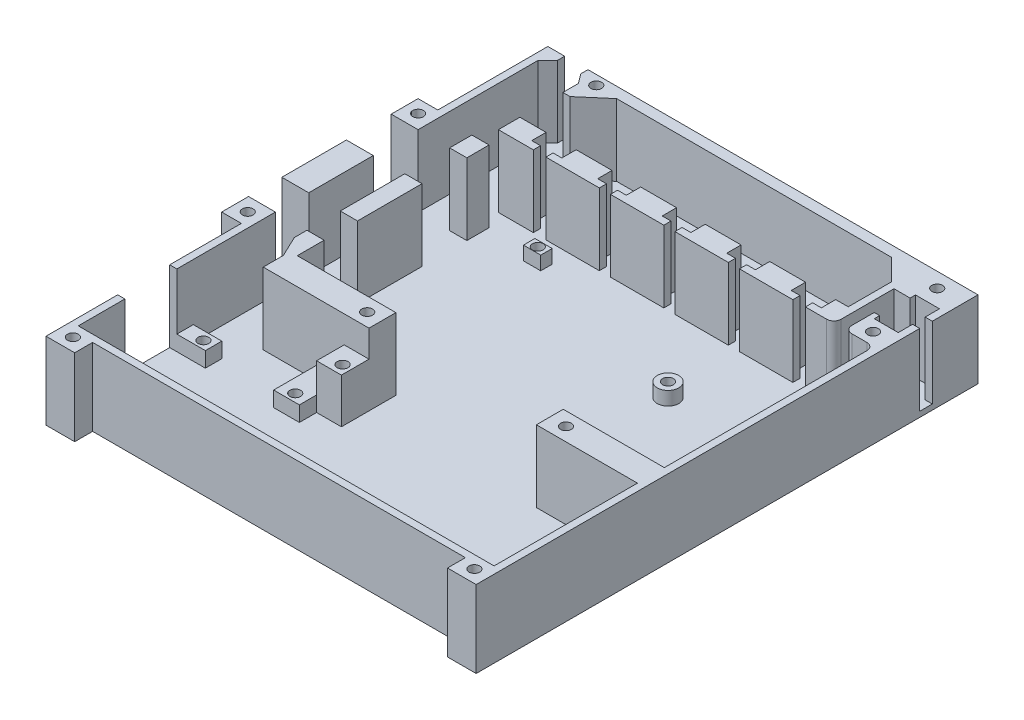
SolidWorks part; units mm, degrees
ref_plane "Front Plane" through (0, 0, 0) normal (0, 0, 1) x (1, 0, 0)
ref_plane "Top Plane" through (0, 0, 0) normal (0, 1, 0) x (1, 0, 0)
ref_plane "Right Plane" through (0, 0, 0) normal (1, 0, 0) x (0, 0, -1)
sketch "Sketch1" plane through (0, 0, 0) normal (0, 1, 0) x (1, 0, 0)
  line L0 (-60, -67.5) -> (-60, -72.5)
  line L1 (-52, -67.5) -> (52, -67.5)
  line L2 (-60, -67.5) -> (-60, -18)
  line L3 (-60, 67.5) -> (60, 67.5)
  line L4 (60, -67.5) -> (60, 67.5)
  line L5 (-60, -67.5) -> (60, 67.5) construction
  line L6 (-60, 67.5) -> (60, -67.5) construction
  line L7 (-60, -72.5) -> (-52, -72.5)
  line L8 (-52, -72.5) -> (-52, -67.5)
  line L9 (0, 0) -> (0, -67.5) construction
  line L10 (60, -67.5) -> (60, -72.5)
  line L11 (52, -72.5) -> (52, -67.5)
  line L12 (60, -72.5) -> (52, -72.5)
  line L13 (-60, -18) -> (-65.5, -18)
  line L14 (-65.5, -18) -> (-65.5, -10.5)
  line L16 (-60, 7.8) -> (60, 7.8) construction
  line L18 (-65.5, -1.2) -> (-60, -1.2)
  line L25 (-60, -10.5) -> (-60, -1.2)
  line L26 (-65.5, -1.2) -> (-65.5, 7.8)
  line L29 (-65.5, -10.5) -> (-60, -10.5)
  line L33 (-65.5, -10.5) -> (-65.5, -4.4868) construction
  line L34 (-65.5, 7.8) -> (-65.5, 16.8)
  line L35 (-65.5, 16.8) -> (-60, 16.8)
  line L36 (-60, 16.8) -> (-60, 29.3)
  line L37 (-60, 29.3) -> (-65.5, 29.3)
  line L38 (-65.5, 29.3) -> (-65.5, 36.8)
  line L39 (-65.5, 36.8) -> (-60, 36.8)
  line L40 (-60, 36.8) -> (-60, 67.5)
  point P0 (0, 0)
  point P30 (-65.5, 7.8)
  dimension "D1" = 120
  dimension "D2" = 135
  dimension "D3" = 5
  dimension "D4" = 8
  dimension "D5" = 54.5
  dimension "D7" = 5.5
  dimension "D8" = 9
  dimension "D9" = 59.7
  dimension "D10" = 9.3
extrude "Boss-Extrude1" add sketch "Sketch1" along normal blind 1.5
sketch "Sketch2" plane through (0, 1.5, 0) normal (0, 1, 0) x (1, 0, 0)
  line L0 (-58, 62.8) -> (-58, 29.3)
  line L1 (-58, -65.5) -> (58, -65.5)
  line L2 (58, -65.5) -> (58, -25.5)
  line L4 (-60, 29.3) -> (-58, 29.3)
  line L5 (-60, 16.8) -> (-58, 16.8)
  line L6 (-58, 16.8) -> (-58, -1.2)
  line L7 (-60, -1.2) -> (-58, -1.2)
  line L8 (-60, -10.5) -> (-58, -10.5)
  line L9 (-58, -10.5) -> (-58, -38)
  line L10 (-55.3, 65.5) -> (-55.3, 67.5)
  line L11 (-48.8, 67.5) -> (-48.8, 65.5)
  line L12 (-55.3, 65.5) -> (-58, 62.8)
  line L13 (-55.3, 67.5) -> (-60, 67.5)
  line L14 (-55.3, 67.5) -> (-48.8, 67.5) construction
  line L15 (-48.8, 65.5) -> (-46.8, 62.8)
  line L16 (-58, 62.8) -> (-46.8, 62.8) construction
  line L17 (-48.8, 67.5) -> (-46.8, 67.5) construction
  line L18 (-46.8, 67.5) -> (-46.8, 58.5) construction
  line L19 (-46.8, 62.8) -> (-46.8, 58.5)
  line L20 (60, -72.5) -> (60, 67.5)
  line L21 (60, 67.5) -> (-60, 67.5)
  line L22 (-60, 67.5) -> (-60, 36.8)
  line L23 (-60, 29.3) -> (-60, 16.8)
  line L24 (-60, 67.5) -> (-60, 36.8)
  line L25 (-60, 36.8) -> (-65.5, 36.8)
  line L26 (-60, 36.8) -> (-65.5, 36.8)
  line L27 (-65.5, 36.8) -> (-65.5, 29.3)
  line L28 (-65.5, 16.8) -> (-65.5, -1.2)
  line L29 (-65.5, -1.2) -> (-60, -1.2)
  line L30 (-60, -1.2) -> (-60, -10.5)
  line L31 (-60, -10.5) -> (-65.5, -10.5)
  line L32 (-65.5, -10.5) -> (-65.5, -18)
  line L33 (-65.5, -18) -> (-60, -18)
  line L34 (-60, -18) -> (-60, -72.5)
  line L35 (-60, -72.5) -> (-52, -72.5)
  line L36 (-52, -72.5) -> (-52, -67.5)
  line L37 (-52, -67.5) -> (52, -67.5)
  line L38 (52, -67.5) -> (52, -72.5)
  line L39 (52, -72.5) -> (60, -72.5)
  line L40 (60, -72.5) -> (60, 51.25)
  line L41 (60, 67.5) -> (-48.8, 67.5)
  line L48 (-65.5, 16.8) -> (-65.5, -1.2)
  line L49 (-65.5, -1.2) -> (-60, -1.2)
  line L51 (-60, -10.5) -> (-65.5, -10.5)
  line L52 (-65.5, -10.5) -> (-65.5, -18)
  line L53 (-65.5, -18) -> (-60, -18)
  line L54 (-60, -18) -> (-60, -38)
  line L55 (-60, -72.5) -> (-52, -72.5)
  line L56 (-52, -72.5) -> (-52, -67.5)
  line L57 (-52, -67.5) -> (52, -67.5)
  line L58 (52, -67.5) -> (52, -72.5)
  line L59 (52, -72.5) -> (60, -72.5)
  line L60 (-46.8, 58.5) -> (-44.8, 58.5)
  line L61 (-44.8, 58.5) -> (-37.8, 64.5)
  line L62 (-46.8, 58.5) -> (-46.8, 46.5) construction
  line L63 (-46.8, 46.5) -> (-39.5, 46.5)
  line L64 (-39.5, 46.5) -> (-39.5, 42.5)
  line L65 (-39.5, 42.5) -> (-37.05, 42.5)
  line L66 (-37.05, 42.5) -> (-37.05, 40.5)
  line L67 (-37.05, 40.5) -> (-46.8, 40.5)
  line L68 (-46.8, 40.5) -> (-46.8, 46.5)
  line L69 (-46.8, 52.5) -> (-35.3, 52.5) construction
  line L70 (-35.3, 52.5) -> (-35.3, 40.5) construction
  line L71 (-35.3, 40.5) -> (-37.05, 40.5) construction
  line L78 (-33.55, 42.5) -> (-33.55, 40.5)
  line L79 (-31.1, 42.5) -> (-33.55, 42.5)
  line L80 (-31.1, 46.5) -> (-31.1, 42.5)
  line L81 (-31.1, 46.5) -> (-21.1, 46.5)
  line L82 (-26.1, 46.5) -> (-26.1, 40.6) construction
  line L83 (-18.65, 42.5) -> (-18.65, 40.5)
  line L84 (-21.1, 42.5) -> (-18.65, 42.5)
  line L85 (-21.1, 46.5) -> (-21.1, 42.5)
  line L86 (-33.55, 40.5) -> (-18.65, 40.5)
  line L87 (-15.55, 40.5) -> (-0.65, 40.5)
  line L88 (-0.65, 42.5) -> (-0.65, 40.5)
  line L89 (-3.1, 42.5) -> (-0.65, 42.5)
  line L90 (-3.1, 46.5) -> (-3.1, 42.5)
  line L91 (-13.1, 46.5) -> (-3.1, 46.5)
  line L92 (-13.1, 46.5) -> (-13.1, 42.5)
  line L93 (-13.1, 42.5) -> (-15.55, 42.5)
  line L94 (-15.55, 42.5) -> (-15.55, 40.5)
  line L95 (2.45, 40.5) -> (17.35, 40.5)
  line L96 (17.35, 42.5) -> (17.35, 40.5)
  line L97 (14.9, 42.5) -> (17.35, 42.5)
  line L98 (14.9, 46.5) -> (14.9, 42.5)
  line L99 (4.9, 46.5) -> (14.9, 46.5)
  line L100 (4.9, 46.5) -> (4.9, 42.5)
  line L101 (4.9, 42.5) -> (2.45, 42.5)
  line L102 (2.45, 42.5) -> (2.45, 40.5)
  line L103 (20.45, 40.5) -> (35.35, 40.5)
  line L104 (35.35, 42.5) -> (35.35, 40.5)
  line L105 (32.9, 42.5) -> (35.35, 42.5)
  line L106 (32.9, 46.5) -> (32.9, 42.5)
  line L107 (22.9, 46.5) -> (32.9, 46.5)
  line L108 (22.9, 46.5) -> (22.9, 42.5)
  line L109 (22.9, 42.5) -> (20.45, 42.5)
  line L110 (20.45, 42.5) -> (20.45, 40.5)
  line L111 (35.35, 40.5) -> (37.1, 40.5) construction
  line L112 (37.1, 40.5) -> (37.1, 46.5) construction
  line L113 (38.85, 42.5) -> (38.85, 40.5)
  line L114 (41.3, 42.5) -> (38.85, 42.5)
  line L115 (41.3, 46.5) -> (41.3, 42.5)
  line L116 (38.85, 40.5) -> (44.8, 40.5)
  line L117 (41.3, 46.5) -> (44.8, 46.5)
  line L118 (46.8, 46.5) -> (46.8, 42.5)
  line L119 (46.8, 46.5) -> (46.8, 57.25)
  line L120 (46.8, 57.25) -> (51.3, 57.25)
  line L121 (51.3, 57.25) -> (51.3, 58.75)
  line L122 (51.3, 58.75) -> (58, 58.75)
  line L123 (44.8, 46.5) -> (44.8, 58.5)
  line L124 (58, 54.75) -> (60, 54.75)
  line L125 (58, 51.25) -> (60, 51.25)
  line L126 (58, 54.75) -> (58, 58.75)
  line L127 (60, 54.75) -> (60, 67.5)
  line L128 (44.8, 58.5) -> (38.8, 64.5)
  line L129 (38.8, 64.5) -> (-37.8, 64.5)
  line L130 (60, 54.75) -> (60, 51.25) construction
  line L131 (60, 53) -> (46.8, 53) construction
  line L132 (49.8, 48.75) -> (51.3, 48.75)
  line L133 (51.3, 48.75) -> (51.3, 47.25)
  line L134 (51.3, 47.25) -> (58, 47.25)
  line L135 (49.8, 48.75) -> (49.8, 42.5)
  line L136 (51.8, 40.5) -> (56, 40.5)
  line L137 (58, 47.25) -> (58, 51.25)
  line L138 (-46.8, 40.5) -> (-46.8, 35.5) construction
  line L139 (-46.8, 35.5) -> (-49.2, 35.5)
  line L140 (-49.2, 35.5) -> (-49.2, 29.3)
  line L141 (-49.2, 29.3) -> (-44.4, 29.3)
  line L142 (-44.4, 29.3) -> (-44.4, 35.5)
  line L143 (-44.4, 35.5) -> (-46.8, 35.5)
  line L144 (-46.8, 29.3) -> (-46.8, 35.5) construction
  line L145 (-58, 29.3) -> (-49.2, 29.3) construction
  line L146 (-58, 16.8) -> (-49.2, 16.8) construction
  line L147 (-58, -10.5) -> (-49.2, -10.5) construction
  line L148 (-49.2, 16.8) -> (-44.4, 16.8)
  line L149 (-49.2, 16.8) -> (-49.2, -1.2)
  line L150 (-49.2, -1.2) -> (-44.4, -1.2)
  line L151 (-44.4, 16.8) -> (-44.4, -1.2)
  line L152 (-49.2, -10.5) -> (-44.4, -10.5)
  line L153 (-44.4, -10.5) -> (-44.4, -18)
  line L154 (-44.4, -18) -> (-16.9, -18)
  line L155 (-16.9, -18) -> (-16.9, -25.5)
  line L156 (-16.9, -25.5) -> (-46.4, -25.5)
  line L157 (-46.4, -25.5) -> (-46.4, -19.9)
  line L158 (-46.4, -19.9) -> (-49.2, -14)
  line L159 (-49.2, -14) -> (-49.2, -10.5)
  line L160 (-60, -18) -> (-44.4, -18) construction
  line L161 (-44.4, -10.5) -> (-44.4, -1.2) construction
  line L162 (-44.4, 16.8) -> (-44.4, 29.3) construction
  line L163 (58, -18) -> (29.8, -18)
  line L164 (29.8, -18) -> (29.8, -25.5)
  line L165 (29.8, -25.5) -> (58, -25.5)
  line L166 (58, -18) -> (58, 38.5)
  line L167 (-60, -52.5) -> (-58, -52.5)
  line L168 (-58, -38) -> (-60, -38)
  line L169 (-60, -52.5) -> (-60, -72.5)
  line L170 (-58, -52.5) -> (-58, -65.5)
  line L187 (-65.5, 36.8) -> (-65.5, 29.3)
  line L188 (-65.5, 29.3) -> (-60, 29.3)
  line L189 (-65.5, 29.3) -> (-60, 29.3)
  line L190 (-60, 16.8) -> (-65.5, 16.8)
  line L191 (-60, 16.8) -> (-65.5, 16.8)
  arc A0 (46.8, 42.5) -> (44.8, 40.5) centre (44.8, 42.5) cw
  arc A1 (56, 40.5) -> (58, 38.5) centre (56, 38.5) cw
  arc A2 (49.8, 42.5) -> (51.8, 40.5) centre (51.8, 42.5) ccw
  point P140 (-59, -52.5)
  dimension "D20" = 2
  dimension "D28" = 2
  dimension "D4" = 2
  dimension "D5" = 2
  dimension "D6" = 20
  dimension "D7" = 6.5
  dimension "D8" = 2
  dimension "D9" = 9
  dimension "D10" = 2
  dimension "D11" = 6
  dimension "D12" = 2
  dimension "D13" = 4.2
  dimension "D14" = 11.5
  dimension "D15" = 10
  dimension "D16" = 1.75
  dimension "D17" = 4
  dimension "D18" = 1.75
  dimension "D19" = 5.5
  dimension "D21" = 2
  dimension "D22" = 10.75
  dimension "D23" = 4.5
  dimension "D24" = 1.5
  dimension "D25" = 4
  dimension "D26" = 3.5
  dimension "D27" = 3
  dimension "D29" = 4.8
  dimension "D30" = 6.2
  dimension "D31" = 3.5
  dimension "D32" = 7.5
  dimension "D33" = 2
  dimension "D34" = 29.5
  dimension "D35" = 28.2
  dimension "D36" = 14.5
  dimension "D1" = 0
extrude "Boss-Extrude2" add sketch "Sketch2" along normal blind 20
sketch "Sketch3" plane through (0, 21.5, 0) normal (0, 1, 0) x (1, 0, 0)
  line L2 (29.8, -21.75) -> (34.3, -21.75) construction
  line L3 (29.8, -18) -> (29.8, -25.5) construction
  line L4 (-56, -72.5) -> (-56, -69) construction
  line L5 (-60, -72.5) -> (-52, -72.5) construction
  line L6 (56, -72.5) -> (56, -69) construction
  line L7 (52, -72.5) -> (60, -72.5) construction
  circle A0 centre (52.7747, 63.3545) radius 1.5
  circle A1 centre (-43.8427, 64.8545) radius 1.5
  circle A2 centre (-61.8793, 33.1911) radius 1.5
  circle A3 centre (-61.8793, -14.3376) radius 1.5
  circle A4 centre (54.2747, 43.9451) radius 1.5
  circle A5 centre (-21.0296, -21.8624) radius 1.5
  circle A6 centre (34.3, -21.75) radius 1.5
  circle A7 centre (-56, -69) radius 1.5
  circle A8 centre (56, -69) radius 1.5
  point P10 (-21.0296, -21.8624)
  point P12 (-61.8793, 33.5924)
  point P14 (-61.8793, -14.3376)
  point P15 (-61.75, 33.1911)
  point P31 (-21.4, -28.75)
  dimension "D2" = 4.5
extrude "Cut-Extrude1" cut sketch "Sketch3" against normal blind 20
sketch "Sketch4" plane through (0, 1.5, 0) normal (0, 1, 0) x (1, 0, 0)
  line L0 (-60, 33.9) -> (-29.2, 33.9) construction
  line L1 (-60, 67.5) -> (-60, 40.6) construction
  line L2 (-29.2, 33.9) -> (-29.2, 67.5) construction
  line L3 (60, 67.5) -> (-48.8, 67.5) construction
  line L4 (-44.4, 35.5) -> (-31.6143, 35.5) construction
  line L5 (-31.6143, 32.3) -> (-26.7857, 32.3)
  line L6 (-31.6143, 32.3) -> (-31.6143, 35.5)
  line L7 (-31.6143, 35.5) -> (-26.7857, 35.5)
  line L8 (-26.7857, 32.3) -> (-26.7857, 35.5)
  line L9 (-31.6143, 32.3) -> (-26.7857, 35.5) construction
  line L10 (-31.6143, 35.5) -> (-26.7857, 32.3) construction
  line L11 (-60, -14.4) -> (-30.3, -14.4) construction
  line L12 (-30.3, -14.4) -> (51.8, -14.4) construction
  line L13 (-60, -18) -> (-60, -38) construction
  line L14 (-30.3, -14.4) -> (-30.3, -67.5) construction
  line L15 (-52, -67.5) -> (52, -67.5) construction
  line L16 (51.8, -14.4) -> (58, -14.4) construction
  line L22 (-16.9, -18) -> (-44.4, -18) construction
  line L23 (-33.1673, -18) -> (-27.3378, -18)
  line L24 (58, 38.5) -> (58, -18) construction
  line L25 (58, -18) -> (29.8, -18) construction
  line L26 (49.4239, -18) -> (54.0138, -18)
  line L27 (49.4239, -18) -> (49.4239, -12.2974)
  line L28 (49.4239, -12.2974) -> (54.0138, -12.2974)
  line L29 (54.0138, -18) -> (54.0138, -12.2974)
  line L30 (-33.1673, -18) -> (-33.1673, -12.2974)
  line L31 (-33.1673, -12.2974) -> (-27.3378, -12.2974)
  line L32 (-27.3378, -18) -> (-27.3378, -12.2974)
  line L33 (-30.3, -14.4) -> (21.5448, -8.3205) construction
  line L34 (21.5448, -8.3205) -> (51.8, -14.4) construction
  line L35 (21.5448, -8.3205) -> (21.5448, 19.4795) construction
  circle A0 centre (-29.2, 33.9) radius 1.5
  circle A1 centre (-30.3, -14.4) radius 1.5
  circle A2 centre (51.8, -14.4) radius 1.5
  circle A3 centre (21.5448, -8.3205) radius 1.5
  circle A4 centre (21.5448, -8.3205) radius 3
  circle A5 centre (21.5448, 19.4795) radius 1.5
  circle A6 centre (21.5448, 19.4795) radius 3
  dimension "D3" = 29.7
  dimension "D6" = 3
  dimension "D7" = 3
  dimension "D1" = 33.6
  dimension "D2" = 30.8
  dimension "D4" = 53.1
  dimension "D5" = 6.2
  dimension "D8" = 30.86
  dimension "D9" = 52.2
extrude "Boss-Extrude3" add sketch "Sketch4" along normal blind 3.8
sketch "Sketch5" plane through (0, 1.5, 0) normal (0, 1, 0) x (1, 0, 0)
  line L0 (-60, -35.8) -> (-27.1736, -35.8) construction
  line L1 (-60, -18) -> (-60, -38) construction
  line L2 (-27.1736, -35.8) -> (-27.1736, -67.5) construction
  line L3 (-52, -67.5) -> (52, -67.5) construction
  line L4 (-27.1736, -67.5) -> (-27.1736, -54.7) construction
  line L5 (-27.1736, -35.8) -> (-52.7736, -35.8) construction
  line L6 (-52.7736, -35.8) -> (-52.7736, -54.7) construction
  line L7 (-52.7736, -54.7) -> (-27.1736, -54.7) construction
  line L8 (-60, -45.25) -> (-52.7736, -45.25) construction
  line L9 (-58, -38) -> (-50.04, -38)
  line L10 (-58, -38) -> (-58, -33.4108)
  line L11 (-58, -33.4108) -> (-50.04, -33.4108)
  line L12 (-50.04, -38) -> (-50.04, -33.4108)
  line L13 (-58, -52.5) -> (-49.4932, -52.5)
  line L14 (-58, -52.5) -> (-58, -57.592)
  line L15 (-58, -57.592) -> (-49.4932, -57.592)
  line L16 (-49.4932, -52.5) -> (-49.4932, -57.592)
  line L17 (-60, -38) -> (-60, -52.5) construction
  line L18 (-46.4, -25.5) -> (-16.9, -25.5) construction
  line L19 (-30.9897, -25.5) -> (-23.8174, -25.5)
  line L20 (-30.9897, -25.5) -> (-30.9897, -38)
  line L21 (-30.9897, -38) -> (-23.8174, -38)
  line L22 (-23.8174, -25.5) -> (-23.8174, -38)
  line L23 (58, -65.5) -> (-58, -65.5) construction
  line L24 (-30.9897, -65.5) -> (-23.8174, -65.5)
  line L25 (-30.9897, -65.5) -> (-30.9897, -52.5)
  line L26 (-30.9897, -52.5) -> (-23.8174, -52.5)
  line L27 (-23.8174, -65.5) -> (-23.8174, -52.5)
  circle A0 centre (-27.1736, -35.8) radius 1.5
  circle A1 centre (-27.1736, -54.7) radius 1.5
  circle A2 centre (-52.7736, -35.8) radius 1.5
  circle A3 centre (-52.7736, -54.7) radius 1.5
  point P29 (-52.7736, -45.25)
  dimension "D2" = 25.6
  dimension "D1" = 31.7
extrude "Boss-Extrude4" add sketch "Sketch5" along normal blind 4.25
sketch "Sketch6" plane through (0, 1.5, 0) normal (0, 1, 0) x (1, 0, 0)
  line L0 (-19.26, -67.5) -> (-19.26, -30.5) construction
  line L1 (-52, -67.5) -> (52, -67.5) construction
  line L2 (-19.26, -30.5) -> (-60, -30.5) construction
  line L3 (-60, -18) -> (-60, -38) construction
  line L4 (-19.26, -67.5) -> (-19.26, -61.1) construction
  line L5 (-19.26, -30.5) -> (55.14, -30.5) construction
  line L6 (55.14, -30.5) -> (55.14, -61.1) construction
  line L7 (55.14, -61.1) -> (-19.26, -61.1) construction
  line L8 (-16.9, -25.5) -> (-16.9, -18) construction
  line L9 (-23.8174, -25.5) -> (-16.9, -25.5)
  line L10 (-23.8174, -25.5) -> (-23.8174, -33.1933)
  line L11 (-23.8174, -33.1933) -> (-16.9, -33.1933)
  line L12 (-16.9, -25.5) -> (-16.9, -33.1933)
  line L14 (58, -25.5) -> (51.9824, -25.5)
  line L15 (58, -25.5) -> (58, -33.1933)
  line L16 (58, -33.1933) -> (51.9824, -33.1933)
  line L17 (51.9824, -25.5) -> (51.9824, -33.1933)
  line L18 (58, -65.5) -> (51.9824, -65.5)
  line L19 (58, -65.5) -> (58, -58.3307)
  line L20 (58, -58.3307) -> (51.9824, -58.3307)
  line L21 (51.9824, -65.5) -> (51.9824, -58.3307)
  line L22 (-23.8174, -65.5) -> (-16.9, -65.5)
  line L23 (-23.8174, -65.5) -> (-23.8174, -58.3307)
  line L24 (-23.8174, -58.3307) -> (-16.9, -58.3307)
  line L25 (-16.9, -65.5) -> (-16.9, -58.3307)
  circle A0 centre (-19.26, -30.5) radius 1.5
  circle A1 centre (-19.26, -61.1) radius 1.5
  circle A2 centre (55.14, -30.5) radius 1.5
  circle A3 centre (55.14, -61.1) radius 1.5
  dimension "D3" = 74.4
  dimension "D1" = 37
  dimension "D2" = 40.74
extrude "Boss-Extrude5" add sketch "Sketch6" along normal blind 12.5
